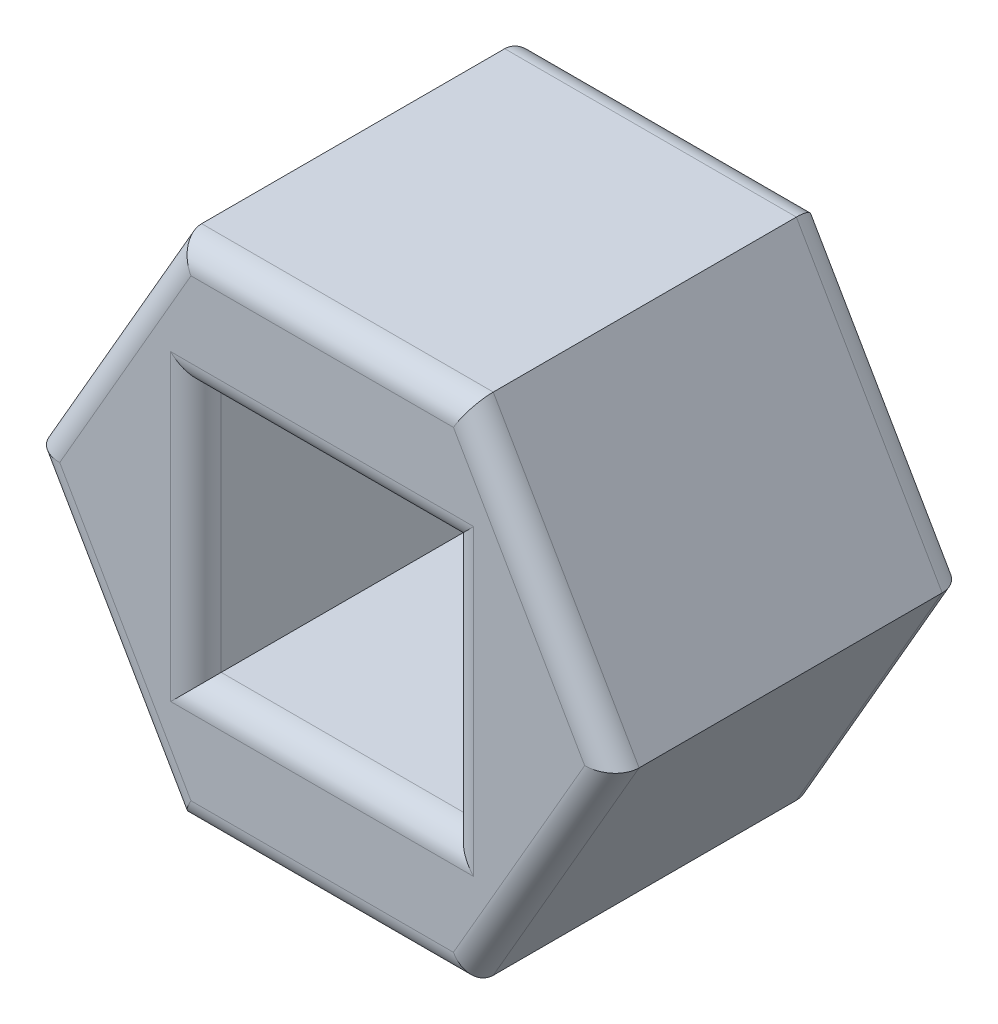
SolidWorks part; units mm, degrees
ref_plane "Front Plane" through (0, 0, 0) normal (0, 0, 1) x (1, 0, 0)
ref_plane "Top Plane" through (0, 0, 0) normal (0, 1, 0) x (1, 0, 0)
ref_plane "Right Plane" through (0, 0, 0) normal (1, 0, 0) x (0, 0, -1)
sketch "Sketch1" plane through (0, 0, 0) normal (0, 0, 1) x (1, 0, 0)
  line L1 (-3.175, -3.175) -> (3.175, -3.175)
  line L2 (-3.175, -3.175) -> (-3.175, 3.175)
  line L3 (-3.175, 3.175) -> (3.175, 3.175)
  line L4 (3.175, -3.175) -> (3.175, 3.175)
  line L5 (-3.175, -3.175) -> (3.175, 3.175) construction
  line L6 (-3.175, 3.175) -> (3.175, -3.175) construction
  line L7 (7.3323, 0) -> (3.6662, 6.35)
  line L8 (3.6662, 6.35) -> (-3.6662, 6.35)
  line L9 (-3.6662, 6.35) -> (-7.3323, 0)
  line L10 (-7.3323, 0) -> (-3.6662, -6.35)
  line L11 (-3.6662, -6.35) -> (3.6662, -6.35)
  line L12 (3.6662, -6.35) -> (7.3323, 0)
  circle A1 centre (0, 0) radius 6.35 construction
  point P0 (0, 0)
  dimension "D1" = 6.35
  dimension "D2" = 6.35
  dimension "D3" = 12.7
extrude "Boss-Extrude1" add sketch "Sketch1" along normal blind 8.89
fillet "Fillet1" radius 0.635 20 edges at (0, -3.175, 0) (-3.175, 0, 0) (0, 3.175, 0) (3.175, 0, 0) (5.4993, 3.175, 0) (0, 6.35, 0) (-5.4993, 3.175, 0) (-5.4993, -3.175, 0) (0, -6.35, 0) (5.4993, -3.175, 0) (-3.175, 0, 8.89) (0, -3.175, 8.89) (3.175, 0, 8.89) (0, 3.175, 8.89) (0, -6.35, 8.89) (-5.4993, -3.175, 8.89) (-5.4993, 3.175, 8.89) (0, 6.35, 8.89) (5.4993, 3.175, 8.89) (5.4993, -3.175, 8.89)
